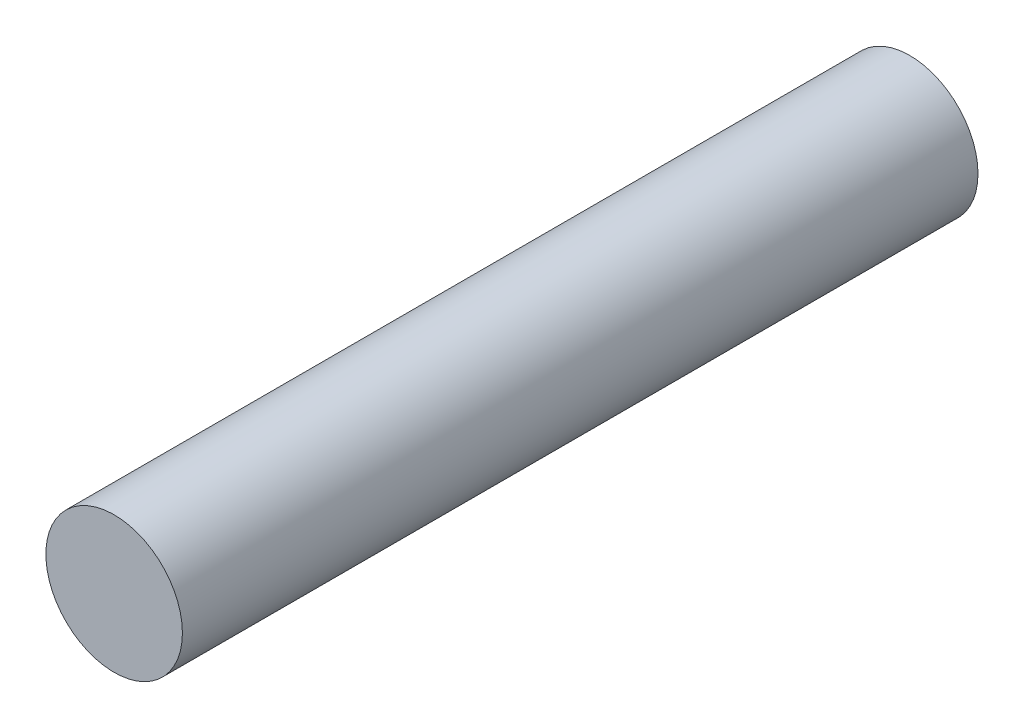
SolidWorks part; units mm, degrees
ref_plane "Alzado" through (0, 0, 0) normal (0, 0, 1) x (1, 0, 0)
ref_plane "Planta" through (0, 0, 0) normal (0, 1, 0) x (1, 0, 0)
ref_plane "Vista lateral" through (0, 0, 0) normal (1, 0, 0) x (0, 0, -1)
sketch "Croquis1" plane through (0, 0, 0) normal (0, 0, 1) x (1, 0, 0)
  circle A0 centre (0, 0) radius 3.175
  dimension "D1" = 6.35
extrude "Saliente-Extruir1" add sketch "Croquis1" along normal mid plane 37
